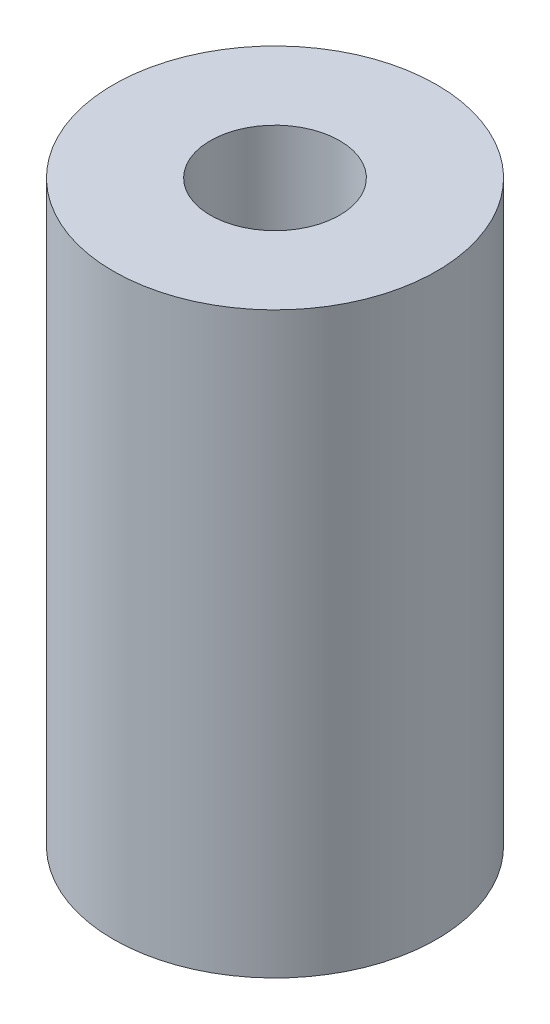
SolidWorks part; units mm, degrees
material "5052-H34"
ref_plane "正面" through (0, 0, 0) normal (0, 0, 1) x (1, 0, 0)
ref_plane "平面" through (0, 0, 0) normal (0, 1, 0) x (1, 0, 0)
ref_plane "右側面" through (0, 0, 0) normal (1, 0, 0) x (0, 0, -1)
sketch "ｽｹｯﾁ1" plane through (0, 0, 0) normal (0, 1, 0) x (1, 0, 0)
  circle A0 centre (0, 0) radius 5
  circle A1 centre (0, 0) radius 2
  dimension "D1" = 4
  dimension "D2" = 10
extrude "ﾎﾞｽ - 押し出し1" add sketch "ｽｹｯﾁ1" along normal blind 17.9
